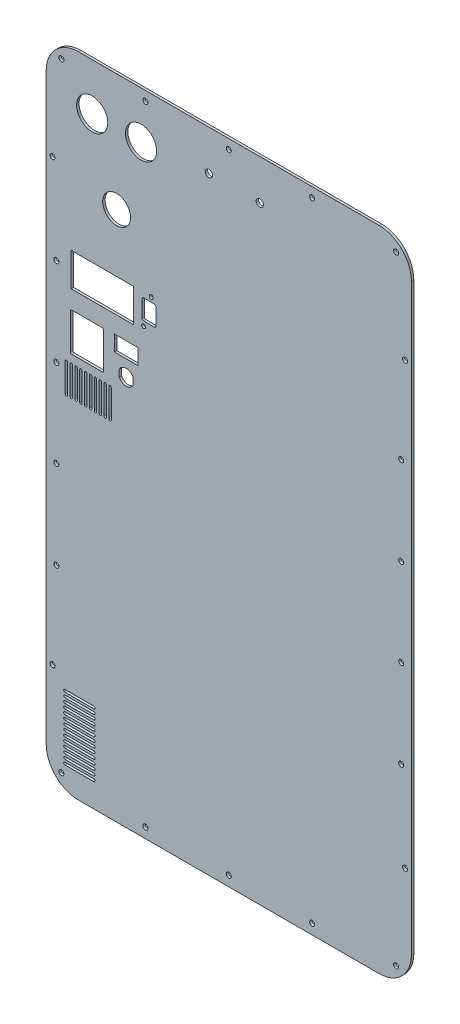
SolidWorks part; units mm, degrees
ref_plane "Alzado" through (0, 0, 0) normal (0, 0, 1) x (1, 0, 0)
ref_plane "Planta" through (0, 0, 0) normal (0, 1, 0) x (1, 0, 0)
ref_plane "Vista lateral" through (0, 0, 0) normal (1, 0, 0) x (0, 0, -1)
sketch "Croquis2" plane through (0, 0, 0) normal (0, 0, 1) x (1, 0, 0)
  line L0 (0, 293.0945) -> (0, 198.6619) construction
  line L1 (-123.95, -267.345) -> (123.95, -267.345)
  line L2 (-150.66, -240.635) -> (-150.66, 240.635)
  line L3 (-123.95, 267.345) -> (123.95, 267.345)
  line L4 (150.66, -240.635) -> (150.66, 240.635)
  line L5 (-150.66, -267.345) -> (150.66, 267.345) construction
  line L6 (-150.66, 267.345) -> (150.66, -267.345) construction
  line L7 (-166.5708, 0) -> (-33.2419, 0) construction
  arc A0 (-123.95, -267.345) -> (-150.66, -240.635) centre (-123.95, -240.635) cw
  arc A1 (123.95, -267.345) -> (150.66, -240.635) centre (123.95, -240.635) ccw
  arc A2 (123.95, 267.345) -> (150.66, 240.635) centre (123.95, 240.635) cw
  arc A3 (-150.66, 240.635) -> (-123.95, 267.345) centre (-123.95, 240.635) cw
  circle A4 centre (0, 259.475) radius 2.095
  circle A5 centre (-68.8, 259.475) radius 2.095
  circle A6 centre (-138.07, 255.285) radius 2.095
  circle A7 centre (-142.26, 36.35) radius 2.095
  circle A8 centre (-142.26, 109.06) radius 2.095
  circle A9 centre (-145.44, 181.77) radius 2.095
  circle A10 centre (142.26, 36.35) radius 2.095
  circle A11 centre (142.26, 109.06) radius 2.095
  circle A12 centre (145.44, 181.77) radius 2.095
  circle A13 centre (138.07, 255.285) radius 2.095
  circle A14 centre (68.8, 259.475) radius 2.095
  circle A15 centre (142.26, -35.85) radius 2.095
  circle A16 centre (142.26, -108.56) radius 2.095
  circle A17 centre (145.44, -181.27) radius 2.095
  circle A18 centre (138.07, -254.785) radius 2.095
  circle A19 centre (68.8, -258.975) radius 2.095
  circle A20 centre (0, -258.975) radius 2.095
  circle A21 centre (-68.8, -258.975) radius 2.095
  circle A22 centre (-138.07, -254.785) radius 2.095
  circle A23 centre (-145.44, -181.27) radius 2.095
  circle A24 centre (-142.26, -108.56) radius 2.095
  circle A25 centre (-142.26, -35.85) radius 2.095
  point P0 (0, 0)
  dimension "D3" = 26.71
  dimension "D4" = 4.19
  dimension "D5" = 7.87
  dimension "D6" = 68.8
  dimension "D7" = 7.87
  dimension "D8" = 12.06
  dimension "D9" = 12.59
  dimension "D11" = 72.71
  dimension "D12" = 36.35
  dimension "D13" = 8.4
  dimension "D14" = 8.4
  dimension "D15" = 5.22
  dimension "D10" = 72.71
  dimension "D16" = 8.37
  dimension "D17" = 8.37
  dimension "D18" = 8.37
  dimension "D19" = 12.56
  dimension "D20" = 12.56
  dimension "D21" = 86.075
  dimension "D22" = 72.71
  dimension "D23" = 72.71
  dimension "D24" = 8.4
  dimension "D25" = 8.4
  dimension "D26" = 5.22
  dimension "D27" = 12.59
  dimension "D28" = 86.075
  dimension "D29" = 72.71
  dimension "D30" = 72.71
  dimension "D1" = 534.69
  dimension "D2" = 301.32
extrude "Saliente-Extruir1" add sketch "Croquis2" along normal blind 2
sketch "Croquis3" plane through (0, 0, 2) normal (0, 0, 1) x (1, 0, 0)
  line L0 (123.95, 267.345) -> (-123.95, 267.345) construction
  line L1 (-150.66, 240.635) -> (-150.66, -240.635) construction
  line L2 (-78.8456, 57.0745) -> (-78.8444, 57.075)
  line L3 (-130.12, 122.465) -> (-78.82, 122.465)
  line L4 (-130.12, 122.465) -> (-130.12, 94.965)
  line L5 (-130.12, 94.965) -> (-78.82, 94.965)
  line L6 (-78.82, 122.465) -> (-78.82, 94.965)
  line L7 (-129.72, 80.025) -> (-104.42, 80.025)
  line L8 (-130.72, 79.025) -> (-130.72, 49.425)
  line L9 (-129.72, 48.425) -> (-104.42, 48.425)
  line L10 (-103.42, 79.025) -> (-103.42, 49.425)
  line L11 (-94.33, 80.525) -> (-75.03, 80.525)
  line L12 (-94.33, 80.525) -> (-94.33, 67.625)
  line L13 (-94.33, 67.625) -> (-75.03, 67.625)
  line L14 (-75.03, 80.525) -> (-75.03, 67.625)
  line L15 (-78.8444, 51.775) -> (-78.8456, 51.7755)
  line L16 (-90.4956, 51.775) -> (-90.4956, 57.075)
  line L17 (-71.59, 110.1) -> (-60.04, 110.1) construction
  line L18 (-78.8456, 51.7755) -> (-78.8456, 57.0745)
  line L19 (-90.4956, 51.775) -> (-78.8456, 57.0745) construction
  line L20 (-90.4956, 57.075) -> (-78.8456, 51.7755) construction
  line L21 (-70.21, 118.375) -> (-61.42, 118.375)
  line L22 (-71.59, 116.995) -> (-71.59, 103.205)
  line L23 (-70.21, 101.825) -> (-61.42, 101.825)
  line L24 (-60.04, 116.995) -> (-60.04, 103.205)
  line L25 (-65.815, 118.375) -> (-65.815, 101.825) construction
  circle A0 centre (-112.69, 228.595) radius 12.85
  circle A1 centre (-72.42, 228.595) radius 12.85
  circle A2 centre (-16.43, 234.145) radius 3
  circle A3 centre (25.57, 234.145) radius 3
  circle A4 centre (-92.56, 170.375) radius 11.5
  arc A5 (-130.72, 49.425) -> (-129.72, 48.425) centre (-129.72, 49.425) ccw
  arc A6 (-104.42, 48.425) -> (-103.42, 49.425) centre (-104.42, 49.425) ccw
  arc A7 (-104.42, 80.025) -> (-103.42, 79.025) centre (-104.42, 79.025) cw
  arc A8 (-129.72, 80.025) -> (-130.72, 79.025) centre (-129.72, 79.025) ccw
  arc A9 (-90.4956, 51.775) -> (-78.8444, 51.775) centre (-84.67, 54.425) ccw
  arc A10 (-78.8444, 57.075) -> (-90.4956, 57.075) centre (-84.67, 54.425) ccw
  circle A11 centre (-63.965, 122.1) radius 1.625
  circle A12 centre (-70.315, 98.1) radius 1.625
  arc A13 (-71.59, 103.205) -> (-70.21, 101.825) centre (-70.21, 103.205) ccw
  arc A14 (-61.42, 101.825) -> (-60.04, 103.205) centre (-61.42, 103.205) ccw
  arc A15 (-61.42, 118.375) -> (-60.04, 116.995) centre (-61.42, 116.995) cw
  arc A16 (-70.21, 118.375) -> (-71.59, 116.995) centre (-70.21, 116.995) ccw
  point P22 (-130.72, 64.225)
  dimension "D1" = 23
  dimension "D2" = 25.7
  dimension "D3" = 38.75
  dimension "D4" = 37.97
  dimension "D5" = 40.27
  dimension "D6" = 6
  dimension "D7" = 55.99
  dimension "D8" = 42
  dimension "D9" = 33.2
  dimension "D10" = 58.1
  dimension "D11" = 96.97
  dimension "D20" = 1
  dimension "D25" = 12.8
  dimension "D28" = 65.99
  dimension "D29" = 25.6
  dimension "D32" = 24
  dimension "D33" = 12
  dimension "D34" = 3.25
  dimension "D36" = 6.35
  dimension "D37" = 1.38
  dimension "D12" = 51.3
  dimension "D13" = 27.5
  dimension "D14" = 20.54
  dimension "D15" = 144.88
  dimension "D16" = 27.3
  dimension "D17" = 31.6
  dimension "D18" = 19.94
  dimension "D19" = 14.94
  dimension "D21" = 9.09
  dimension "D22" = 19.3
  dimension "D23" = 12.9
  dimension "D24" = 14.44
  dimension "D26" = 11.65
  dimension "D27" = 5.3
  dimension "D30" = 16.55
  dimension "D31" = 11.55
  dimension "D35" = 1.85
  dimension "D38" = 7.23
  dimension "D39" = 4.09
extrude "Cortar-Extruir1" cut sketch "Croquis3" against normal through all
sketch "Croquis4" plane through (0, 0, 2) normal (0, 0, 1) x (1, 0, 0)
  line L0 (-133.97, 40.945) -> (-133.97, 17.475) construction
  line L1 (-132.97, 40.945) -> (-132.97, 17.475)
  line L2 (-134.97, 40.945) -> (-134.97, 17.475)
  line L3 (-150.66, 240.635) -> (-150.66, -240.635) construction
  line L4 (-129.72, 48.425) -> (-104.42, 48.425) construction
  line L5 (-129.97, 40.945) -> (-129.97, 17.475) construction
  line L6 (-128.97, 40.945) -> (-128.97, 17.475)
  line L7 (-130.97, 40.945) -> (-130.97, 17.475)
  line L8 (-125.97, 40.945) -> (-125.97, 17.475) construction
  line L9 (-124.97, 40.945) -> (-124.97, 17.475)
  line L10 (-126.97, 40.945) -> (-126.97, 17.475)
  line L11 (-121.97, 40.945) -> (-121.97, 17.475) construction
  line L12 (-120.97, 40.945) -> (-120.97, 17.475)
  line L13 (-122.97, 40.945) -> (-122.97, 17.475)
  line L14 (-117.97, 40.945) -> (-117.97, 17.475) construction
  line L15 (-116.97, 40.945) -> (-116.97, 17.475)
  line L16 (-118.97, 40.945) -> (-118.97, 17.475)
  line L17 (-113.97, 40.945) -> (-113.97, 17.475) construction
  line L18 (-112.97, 40.945) -> (-112.97, 17.475)
  line L19 (-114.97, 40.945) -> (-114.97, 17.475)
  line L20 (-109.97, 40.945) -> (-109.97, 17.475) construction
  line L21 (-108.97, 40.945) -> (-108.97, 17.475)
  line L22 (-110.97, 40.945) -> (-110.97, 17.475)
  line L23 (-105.97, 40.945) -> (-105.97, 17.475) construction
  line L24 (-104.97, 40.945) -> (-104.97, 17.475)
  line L25 (-106.97, 40.945) -> (-106.97, 17.475)
  line L26 (-101.97, 40.945) -> (-101.97, 17.475) construction
  line L27 (-100.97, 40.945) -> (-100.97, 17.475)
  line L28 (-102.97, 40.945) -> (-102.97, 17.475)
  line L29 (-97.97, 40.945) -> (-97.97, 17.475) construction
  line L30 (-96.97, 40.945) -> (-96.97, 17.475)
  line L31 (-98.97, 40.945) -> (-98.97, 17.475)
  line L32 (-135.21, -246.835) -> (-111.31, -246.835) construction
  line L33 (-135.21, -245.835) -> (-111.31, -245.835)
  line L34 (-135.21, -247.835) -> (-111.31, -247.835)
  line L35 (-123.95, -267.345) -> (123.95, -267.345) construction
  line L36 (-135.21, -242.835) -> (-111.31, -242.835) construction
  line L37 (-135.21, -241.835) -> (-111.31, -241.835)
  line L38 (-135.21, -243.835) -> (-111.31, -243.835)
  line L39 (-135.21, -238.835) -> (-111.31, -238.835) construction
  line L40 (-135.21, -237.835) -> (-111.31, -237.835)
  line L41 (-135.21, -239.835) -> (-111.31, -239.835)
  line L42 (-135.21, -234.835) -> (-111.31, -234.835) construction
  line L43 (-135.21, -233.835) -> (-111.31, -233.835)
  line L44 (-135.21, -235.835) -> (-111.31, -235.835)
  line L45 (-135.21, -230.835) -> (-111.31, -230.835) construction
  line L46 (-135.21, -229.835) -> (-111.31, -229.835)
  line L47 (-135.21, -231.835) -> (-111.31, -231.835)
  line L48 (-135.21, -226.835) -> (-111.31, -226.835) construction
  line L49 (-135.21, -225.835) -> (-111.31, -225.835)
  line L50 (-135.21, -227.835) -> (-111.31, -227.835)
  line L51 (-135.21, -222.835) -> (-111.31, -222.835) construction
  line L52 (-135.21, -221.835) -> (-111.31, -221.835)
  line L53 (-135.21, -223.835) -> (-111.31, -223.835)
  line L54 (-135.21, -218.835) -> (-111.31, -218.835) construction
  line L55 (-135.21, -217.835) -> (-111.31, -217.835)
  line L56 (-135.21, -219.835) -> (-111.31, -219.835)
  line L57 (-135.21, -214.835) -> (-111.31, -214.835) construction
  line L58 (-135.21, -213.835) -> (-111.31, -213.835)
  line L59 (-135.21, -215.835) -> (-111.31, -215.835)
  line L60 (-135.21, -210.835) -> (-111.31, -210.835) construction
  line L61 (-135.21, -209.835) -> (-111.31, -209.835)
  line L62 (-135.21, -211.835) -> (-111.31, -211.835)
  line L63 (-135.21, -206.835) -> (-111.31, -206.835) construction
  line L64 (-135.21, -205.835) -> (-111.31, -205.835)
  line L65 (-135.21, -207.835) -> (-111.31, -207.835)
  line L66 (-135.21, -202.835) -> (-111.31, -202.835) construction
  line L67 (-135.21, -201.835) -> (-111.31, -201.835)
  line L68 (-135.21, -203.835) -> (-111.31, -203.835)
  line L69 (-135.21, -198.835) -> (-111.31, -198.835) construction
  line L70 (-135.21, -197.835) -> (-111.31, -197.835)
  line L71 (-135.21, -199.835) -> (-111.31, -199.835)
  line L72 (-135.21, -194.835) -> (-111.31, -194.835) construction
  line L73 (-135.21, -193.835) -> (-111.31, -193.835)
  line L74 (-135.21, -195.835) -> (-111.31, -195.835)
  arc A0 (-132.97, 40.945) -> (-134.97, 40.945) centre (-133.97, 40.945) ccw
  arc A1 (-134.97, 17.475) -> (-132.97, 17.475) centre (-133.97, 17.475) ccw
  arc A2 (-128.97, 40.945) -> (-130.97, 40.945) centre (-129.97, 40.945) ccw
  arc A3 (-130.97, 17.475) -> (-128.97, 17.475) centre (-129.97, 17.475) ccw
  arc A4 (-124.97, 40.945) -> (-126.97, 40.945) centre (-125.97, 40.945) ccw
  arc A5 (-126.97, 17.475) -> (-124.97, 17.475) centre (-125.97, 17.475) ccw
  arc A6 (-120.97, 40.945) -> (-122.97, 40.945) centre (-121.97, 40.945) ccw
  arc A7 (-122.97, 17.475) -> (-120.97, 17.475) centre (-121.97, 17.475) ccw
  arc A8 (-116.97, 40.945) -> (-118.97, 40.945) centre (-117.97, 40.945) ccw
  arc A9 (-118.97, 17.475) -> (-116.97, 17.475) centre (-117.97, 17.475) ccw
  arc A10 (-112.97, 40.945) -> (-114.97, 40.945) centre (-113.97, 40.945) ccw
  arc A11 (-114.97, 17.475) -> (-112.97, 17.475) centre (-113.97, 17.475) ccw
  arc A12 (-108.97, 40.945) -> (-110.97, 40.945) centre (-109.97, 40.945) ccw
  arc A13 (-110.97, 17.475) -> (-108.97, 17.475) centre (-109.97, 17.475) ccw
  arc A14 (-104.97, 40.945) -> (-106.97, 40.945) centre (-105.97, 40.945) ccw
  arc A15 (-106.97, 17.475) -> (-104.97, 17.475) centre (-105.97, 17.475) ccw
  arc A16 (-100.97, 40.945) -> (-102.97, 40.945) centre (-101.97, 40.945) ccw
  arc A17 (-102.97, 17.475) -> (-100.97, 17.475) centre (-101.97, 17.475) ccw
  arc A18 (-96.97, 40.945) -> (-98.97, 40.945) centre (-97.97, 40.945) ccw
  arc A19 (-98.97, 17.475) -> (-96.97, 17.475) centre (-97.97, 17.475) ccw
  arc A20 (-135.21, -245.835) -> (-135.21, -247.835) centre (-135.21, -246.835) ccw
  arc A21 (-111.31, -247.835) -> (-111.31, -245.835) centre (-111.31, -246.835) ccw
  arc A22 (-135.21, -241.835) -> (-135.21, -243.835) centre (-135.21, -242.835) ccw
  arc A23 (-111.31, -243.835) -> (-111.31, -241.835) centre (-111.31, -242.835) ccw
  arc A24 (-135.21, -237.835) -> (-135.21, -239.835) centre (-135.21, -238.835) ccw
  arc A25 (-111.31, -239.835) -> (-111.31, -237.835) centre (-111.31, -238.835) ccw
  arc A26 (-135.21, -233.835) -> (-135.21, -235.835) centre (-135.21, -234.835) ccw
  arc A27 (-111.31, -235.835) -> (-111.31, -233.835) centre (-111.31, -234.835) ccw
  arc A28 (-135.21, -229.835) -> (-135.21, -231.835) centre (-135.21, -230.835) ccw
  arc A29 (-111.31, -231.835) -> (-111.31, -229.835) centre (-111.31, -230.835) ccw
  arc A30 (-135.21, -225.835) -> (-135.21, -227.835) centre (-135.21, -226.835) ccw
  arc A31 (-111.31, -227.835) -> (-111.31, -225.835) centre (-111.31, -226.835) ccw
  arc A32 (-135.21, -221.835) -> (-135.21, -223.835) centre (-135.21, -222.835) ccw
  arc A33 (-111.31, -223.835) -> (-111.31, -221.835) centre (-111.31, -222.835) ccw
  arc A34 (-135.21, -217.835) -> (-135.21, -219.835) centre (-135.21, -218.835) ccw
  arc A35 (-111.31, -219.835) -> (-111.31, -217.835) centre (-111.31, -218.835) ccw
  arc A36 (-135.21, -213.835) -> (-135.21, -215.835) centre (-135.21, -214.835) ccw
  arc A37 (-111.31, -215.835) -> (-111.31, -213.835) centre (-111.31, -214.835) ccw
  arc A38 (-135.21, -209.835) -> (-135.21, -211.835) centre (-135.21, -210.835) ccw
  arc A39 (-111.31, -211.835) -> (-111.31, -209.835) centre (-111.31, -210.835) ccw
  arc A40 (-135.21, -205.835) -> (-135.21, -207.835) centre (-135.21, -206.835) ccw
  arc A41 (-111.31, -207.835) -> (-111.31, -205.835) centre (-111.31, -206.835) ccw
  arc A42 (-135.21, -201.835) -> (-135.21, -203.835) centre (-135.21, -202.835) ccw
  arc A43 (-111.31, -203.835) -> (-111.31, -201.835) centre (-111.31, -202.835) ccw
  arc A44 (-135.21, -197.835) -> (-135.21, -199.835) centre (-135.21, -198.835) ccw
  arc A45 (-111.31, -199.835) -> (-111.31, -197.835) centre (-111.31, -198.835) ccw
  arc A46 (-135.21, -193.835) -> (-135.21, -195.835) centre (-135.21, -194.835) ccw
  arc A47 (-111.31, -195.835) -> (-111.31, -193.835) centre (-111.31, -194.835) ccw
  point P2 (-133.97, 29.21)
  point P15 (-129.97, 29.21)
  point P22 (-125.97, 29.21)
  point P29 (-121.97, 29.21)
  point P36 (-117.97, 29.21)
  point P43 (-113.97, 29.21)
  point P50 (-109.97, 29.21)
  point P57 (-105.97, 29.21)
  point P64 (-101.97, 29.21)
  point P71 (-97.97, 29.21)
  point P76 (-123.26, -246.835)
  point P86 (-123.26, -242.835)
  point P93 (-123.26, -238.835)
  point P100 (-123.26, -234.835)
  point P107 (-123.26, -230.835)
  point P114 (-123.26, -226.835)
  point P121 (-123.26, -222.835)
  point P128 (-123.26, -218.835)
  point P135 (-123.26, -214.835)
  point P142 (-123.26, -210.835)
  point P149 (-123.26, -206.835)
  point P156 (-123.26, -202.835)
  point P163 (-123.26, -198.835)
  point P170 (-123.26, -194.835)
  dimension "D1" = 23.47
  dimension "D2" = 2
  dimension "D3" = 15.69
  dimension "D4" = 7.48
  dimension "D6" = 23.9
  dimension "D7" = 2
  dimension "D8" = 15.45
  dimension "D9" = 19.51
  dimension "D5" = 10
  dimension "D10" = 14
extrude "Cortar-Extruir2" cut sketch "Croquis4" against normal through all
